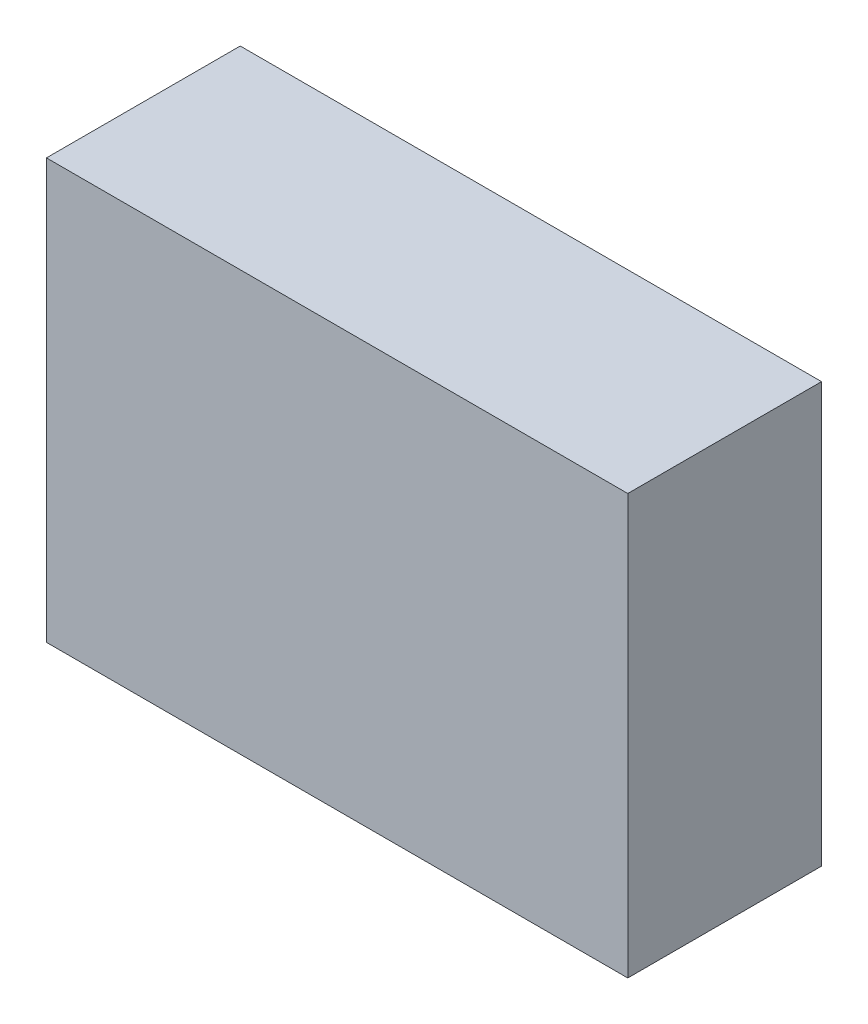
SolidWorks part; units mm, degrees
ref_plane "Front Plane" through (0, 0, 0) normal (0, 0, 1) x (1, 0, 0)
ref_plane "Top Plane" through (0, 0, 0) normal (0, 1, 0) x (1, 0, 0)
ref_plane "Right Plane" through (0, 0, 0) normal (1, 0, 0) x (0, 0, -1)
sketch "Sketch1" plane through (0, 0, 0) normal (0, 1, 0) x (1, 0, 0)
  line L1 (3.81, 1.27) -> (-3.81, 1.27)
  line L2 (3.81, 1.27) -> (3.81, -1.27)
  line L3 (3.81, -1.27) -> (-3.81, -1.27)
  line L4 (-3.81, 1.27) -> (-3.81, -1.27)
  line L5 (3.81, 1.27) -> (-3.81, -1.27) construction
  line L6 (3.81, -1.27) -> (-3.81, 1.27) construction
  point P0 (0, 0)
  dimension "D1" = 7.62
  dimension "D2" = 2.54
extrude "Boss-Extrude1" add sketch "Sketch1" along normal blind 5.5
